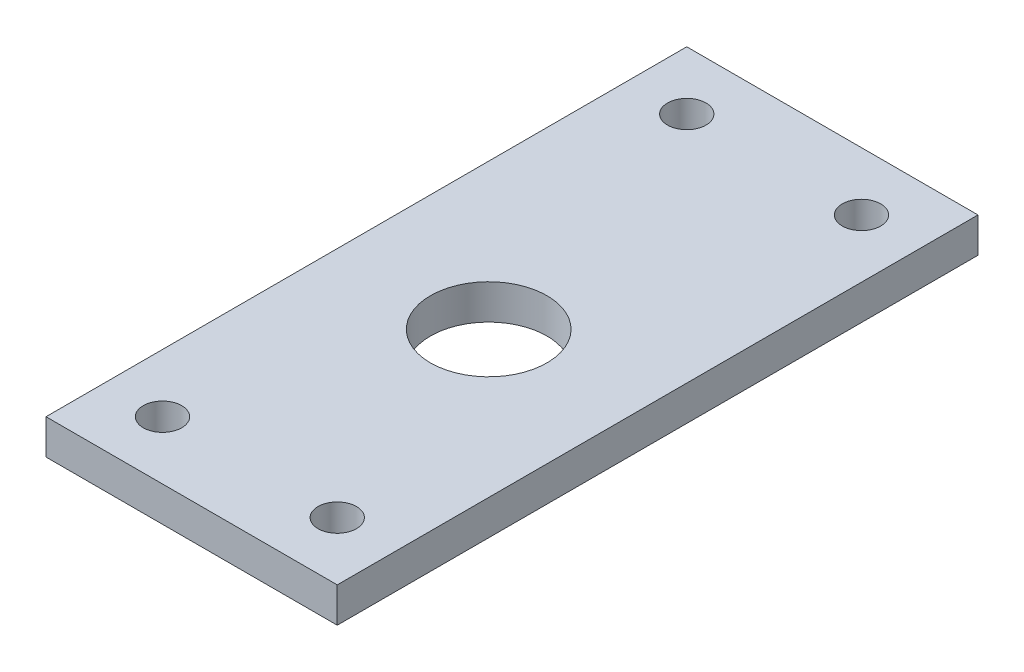
SolidWorks part; units mm, degrees
material "Thornel Mat VMA"
ref_plane "前视基准面" through (0, 0, 0) normal (0, 0, 1) x (1, 0, 0)
ref_plane "上视基准面" through (0, 0, 0) normal (0, 1, 0) x (1, 0, 0)
ref_plane "右视基准面" through (0, 0, 0) normal (1, 0, 0) x (0, 0, -1)
sketch "草图1" plane through (0, 0, 0) normal (0, 1, 0) x (1, 0, 0)
  line L1 (-12.5, 27.5) -> (12.5, 27.5)
  line L2 (-12.5, 27.5) -> (-12.5, -27.5)
  line L3 (-12.5, -27.5) -> (12.5, -27.5)
  line L4 (12.5, 27.5) -> (12.5, -27.5)
  line L5 (-12.5, 27.5) -> (12.5, -27.5) construction
  line L6 (-12.5, -27.5) -> (12.5, 27.5) construction
  point P0 (0, 0)
  dimension "D1" = 55
  dimension "D2" = 25
extrude "凸台-拉伸1" add sketch "草图1" along normal blind 3
sketch "草图2" plane through (0, 3, 0) normal (0, 1, 0) x (1, 0, 0)
  line L0 (-12.5, 27.5) -> (-2.5, 17.5)
  line L1 (-12.5, 27.5) -> (-2.5, 27.5)
  line L2 (-12.5, 27.5) -> (-12.5, 17.5)
  line L3 (-12.5, 17.5) -> (-2.5, 17.5)
  line L4 (-2.5, 27.5) -> (-2.5, 17.5)
  line L5 (12.5, 27.5) -> (2.5, 27.5)
  line L6 (12.5, 27.5) -> (12.5, 17.5)
  line L7 (12.5, 17.5) -> (2.5, 17.5)
  line L8 (2.5, 27.5) -> (2.5, 17.5)
  line L9 (-12.5, -27.5) -> (-2.5, -27.5)
  line L10 (-12.5, -27.5) -> (-12.5, -17.5)
  line L11 (-12.5, -17.5) -> (-2.5, -17.5)
  line L12 (-2.5, -27.5) -> (-2.5, -17.5)
  line L13 (12.5, -27.5) -> (2.5, -27.5)
  line L14 (12.5, -27.5) -> (12.5, -17.5)
  line L15 (12.5, -17.5) -> (2.5, -17.5)
  line L16 (2.5, -27.5) -> (2.5, -17.5)
  line L17 (12.5, 27.5) -> (2.5, 17.5)
  line L18 (-12.5, -27.5) -> (-2.5, -17.5)
  line L19 (12.5, -27.5) -> (2.5, -17.5)
  line L20 (0, 0) -> (0, 2)
  line L21 (0, 0) -> (0, -2)
  dimension "D1" = 10
  dimension "D2" = 10
  dimension "D3" = 10
  dimension "D4" = 10
  dimension "D5" = 10
  dimension "D6" = 10
  dimension "D7" = 10
  dimension "D8" = 10
  dimension "D9" = 2
  dimension "D10" = 2
sketch "草图3" plane through (0, 3, 0) normal (0, 1, 0) x (1, 0, 0)
  line L0 (-12.5, 27.5) -> (-2.5, 17.5) construction
  line L1 (12.5, 27.5) -> (2.5, 17.5) construction
  line L2 (12.5, -27.5) -> (2.5, -17.5) construction
  line L3 (-12.5, -27.5) -> (-2.5, -17.5) construction
  point P0 (-7.5, 22.5)
  point P4 (7.5, 22.5)
  point P8 (7.5, -22.5)
  point P12 (-7.5, -22.5)
hole_wizard "孔1" positions "草图3" profile "草图4" legacy end condition through all
sketch "草图4" plane through (-7.5, 3, -22.5) normal (1, 0, 0) x (0, 0, 1)
  line L0 (0, 0) -> (0, 3)
  line L1 (0, 3) -> (1.65, 3)
  line L2 (1.65, 3) -> (1.65, 0)
  line L3 (1.65, 0) -> (0, 0)
  line L4 (0, 110) -> (0, -10) construction
  dimension "直径" = 3.3
  dimension "深度" = 3
sketch "草图5" plane through (0, 3, 0) normal (0, 1, 0) x (1, 0, 0)
  point P0 (0, 0)
  point P4 (0, -2)
hole_wizard "孔2" positions "草图5" profile "草图6" legacy
sketch "草图6" plane through (0, 3, 2) normal (1, 0, 0) x (0, 0, 1)
  line L0 (0, 0) -> (0, 3)
  line L1 (0, 3) -> (5, 3)
  line L2 (5, 3) -> (5, 0)
  line L3 (5, 0) -> (0, 0)
  line L4 (0, 110) -> (0, -10) construction
  dimension "直径" = 10
  dimension "深度" = 3
